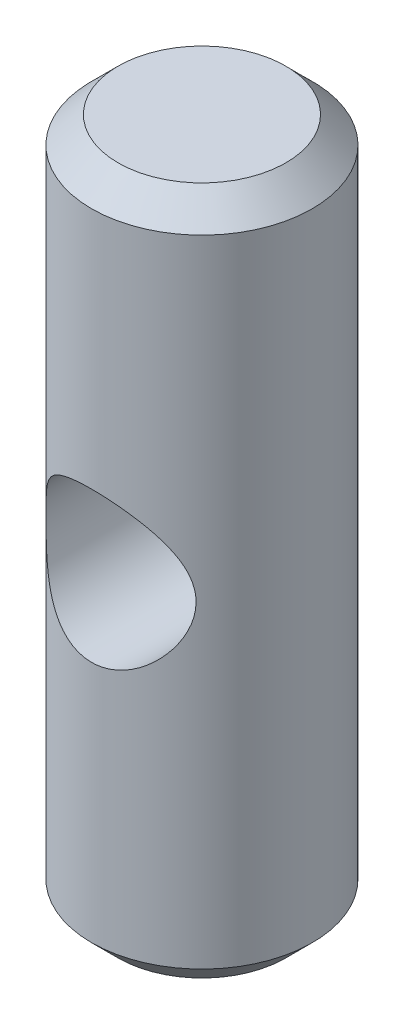
SolidWorks part; units mm, degrees
material "Brass"
ref_plane "Front Plane" through (0, 0, 0) normal (0, 0, 1) x (1, 0, 0)
ref_plane "Top Plane" through (0, 0, 0) normal (0, 1, 0) x (1, 0, 0)
ref_plane "Right Plane" through (0, 0, 0) normal (1, 0, 0) x (0, 0, -1)
sketch "Sketch2" plane through (0, 0, 0) normal (0, 1, 0) x (1, 0, 0)
  circle A0 centre (0, 0) radius 12.5
  dimension "D1" = 25
extrude "Boss-Extrude1" add sketch "Sketch2" along normal mid plane 78
sketch "Sketch3" plane through (0, 0, 0) normal (0, 0, 1) x (1, 0, 0)
  circle A0 centre (0, 0) radius 8.5
  dimension "D1" = 17
extrude "Cut-Extrude1" cut sketch "Sketch3" against normal through all both and the other way through all
chamfer "Chamfer1" distance 3 angle 45 2 edges at (0, -39, 12.5) (0, 39, 12.5)
